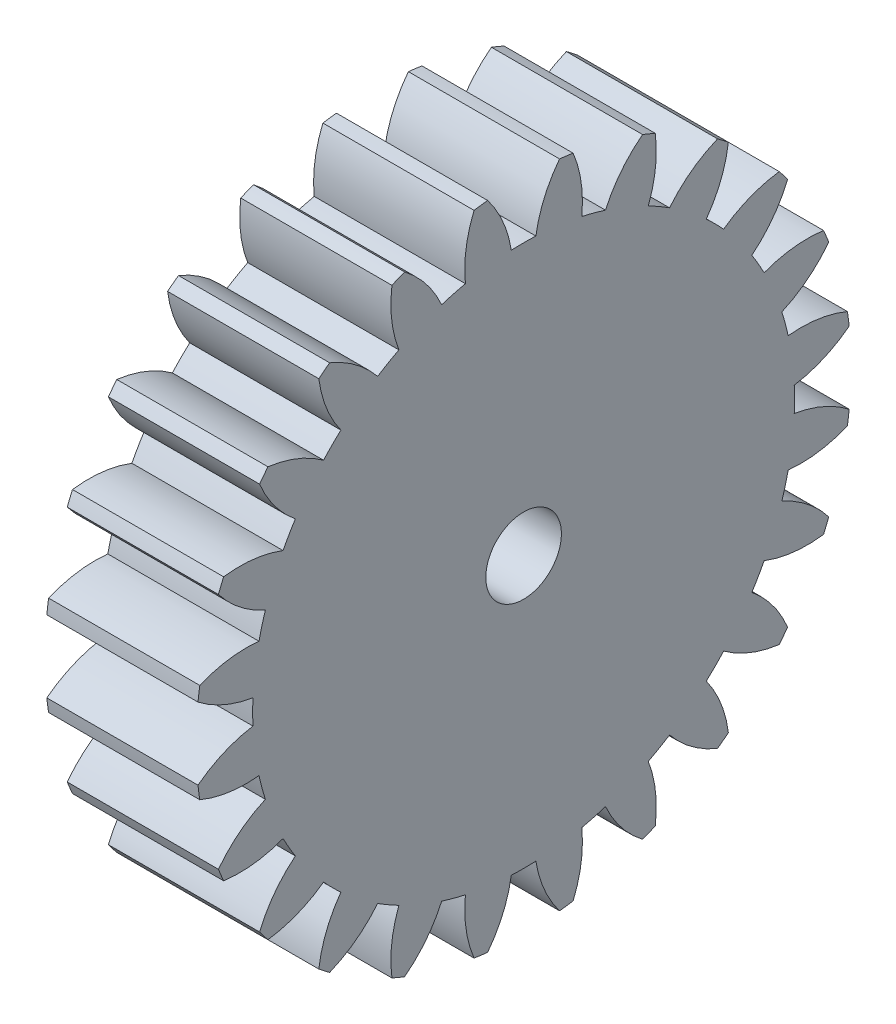
SolidWorks part; units mm, degrees
ref_plane "Plane1" through (0, 0, 0) normal (0, 0, 1) x (1, 0, 0)
ref_plane "Plane2" through (0, 0, 0) normal (0, 1, 0) x (1, 0, 0)
ref_plane "Plane3" through (0, 0, 0) normal (1, 0, 0) x (0, 0, -1)
other "Configuration Table"
sketch "HoldingSke" plane through (0, 0, 0) normal (0, 1, 0) x (1, 0, 0)
  line L0 (0, 0) -> (556.8973, -247.9467)
  line L1 (-15, 0) -> (100, 0) construction
  line L2 (0, 0) -> (-2.1039, 2.3779)
  line L3 (0, 0) -> (-11.863, 4.5341)
  line L4 (0, 0) -> (7.8894, 3.5126)
  line L5 (0, 0) -> (-47.5972, -17.7524)
  line L6 (0, 0) -> (-5.2639, -3.5516)
  line L7 (-2.1039, 2.3779) -> (8.8308, 51.9871)
  line L8 (-76.2, 54.61) -> (-72.771, 54.61)
  line L9 (-71.009, 38.7566) -> (-53.1078, 45.2721)
  line L10 (-76.2, 71.12) -> (104.1128, 71.12)
  line L11 (0, 0) -> (-6.35, 0)
  line L12 (-76.2, 101.6) -> (-76.1573, 101.6)
  line L13 (24.9733, 27.94) -> (52.9518, 28.4284)
  line L14 (24.9733, 27.94) -> (25.0241, 27.9398)
  line L15 (24.9733, 27.94) -> (100.4021, 29.52)
  circle A0 centre (0, 0) radius 1.5875
  circle A1 centre (0, 0) radius 11.3792
  circle A2 centre (0, 0) radius 38.1
  circle A3 centre (0, 0) radius 1.5875
  dimension "MHD" = 22.7584
  dimension "Hub_dia" = 76.2
  dimension "Bore" = 3.175
  dimension "MBD" = 3.175
  dimension "Num_teeth" = 24
  dimension "Pitch" = 609.6
  dimension "Overall_len" = 50.8
  dimension "Show_teeth" = 24
  dimension "Thickness" = 6.35
  dimension "OAL" = 50.8001
  dimension "T_dim" = 3.429
  dimension "Ap" = 20
  dimension "H" = 19.05
  dimension "Pitch_radius" = 180.3128
  dimension "Width" = 6.35
  dimension "Backlash" = 0.0427
  dimension "Addendum_fac" = 1
  dimension "Dedendum_fac" = 1.2
  dimension "Clearance_fac" = 0.2
  dimension "Dedendum_add" = 0.0508
sketch "BasProSke" plane through (0, 0, 0) normal (0, 1, 0) x (1, 0, 0)
  line L0 (-10, 0) -> (60, 0) construction
  line L1 (0, 0) -> (0, 13.7583)
  line L2 (0, 0) -> (6.35, 0)
  line L3 (6.35, 0) -> (6.35, 13.7583)
  line L4 (6.35, 13.7583) -> (0, 13.7583)
  dimension "Thickness" = 6.35
  dimension "Diameter" = 27.5167
revolve "Base-Revolve" add sketch "BasProSke" angle 360 about L0
sketch "TooCutSke" plane through (0, 0, 0) normal (1, 0, 0) x (0, 0, -1)
  line L1 (0, 0) -> (0, 107) construction
  line L2 (0, 0) -> (-0.9053, 12.6677) construction
  line L3 (0, 0) -> (-3.3095, 25.138) construction
  line L4 (-0.9053, 12.6677) -> (-1.6547, 12.569) construction
  arc A0 (0.516, 11.3675) -> (-0.516, 11.3675) centre (0, 0) ccw
  arc A1 (1.5285, 13.6987) -> (-1.5285, 13.6987) centre (0, 0) ccw
  circle A2 centre (0, 0) radius 12.7 construction
  circle A3 centre (0, 0) radius 11.9341 construction
  arc A4 (-0.516, 11.3675) -> (-1.5285, 13.6987) centre (-5.5336, 10.5736) ccw
  arc A5 (1.5285, 13.6987) -> (0.516, 11.3675) centre (5.5336, 10.5736) ccw
  dimension "Root_dia" = 22.7584
  dimension "Overcut_dia" = 27.5675
  dimension "Pitch_dia" = 25.4
  dimension "Base_dia" = 23.8682
  dimension "Flank_rad" = 5.08
  dimension "Half_ang" = 7.5
  dimension "Half_CT" = 0.7559
extrude "ToothCut" cut sketch "TooCutSke" along normal through all
fillet "Breaks" [suppressed] radius 0.0212
fillet "RootFillets" [suppressed] radius 0.2625
pattern_circular "TeethCuts" count 24 every 15 about axis through (-10, 0, 0) along (1, 0, 0) of "ToothCut", "RootFillets", "Breaks"
sketch "HubNeaOneSke" plane through (0, 0, 0) normal (-1, 0, 0) x (0, 0, 1)
  circle A0 centre (0, 0) radius 11.3792
  dimension "Diameter" = 22.7584
extrude "HubNearOne" [suppressed] add sketch "HubNeaOneSke" along normal blind 44.4501
sketch "HubNeaBotSke" plane through (0, 0, 0) normal (-1, 0, 0) x (0, 0, 1)
  circle A0 centre (0, 0) radius 11.3792
  dimension "Diameter" = 22.7584
extrude "HubNearBoth" [suppressed] add sketch "HubNeaBotSke" along normal blind 22.225
ref_plane "FarPln" through (6.35, 0, 0) normal (1, 0, 0) x (0, 0, -1)
sketch "HubFarSke" plane through (6.35, 0, 0) normal (1, 0, 0) x (0, 0, -1)
  circle A0 centre (0, 0) radius 11.3792
  dimension "Diameter" = 22.7584
extrude "HubFar" [suppressed] add sketch "HubFarSke" along normal blind 22.225
sketch "BorSke" plane through (0, 0, 0) normal (1, 0, 0) x (0, 0, -1)
  circle A0 centre (0, 0) radius 1.5875
  dimension "Diameter" = 3.175
extrude "Bore" cut sketch "BorSke" along normal mid plane 101.6001
sketch "KeySke" plane through (0, 0, 0) normal (1, 0, 0) x (0, 0, -1)
  line L0 (-0.127, 0) -> (-0.127, 1.8415)
  line L1 (-0.127, 1.8415) -> (0.127, 1.8415)
  line L2 (0.127, 1.8415) -> (0.127, 0)
  line L3 (0, 0) -> (0, 34) construction
  line L4 (-0.127, 0) -> (0.127, 0)
  dimension "Offset" = 1.8415
  dimension "Width" = 0.254
extrude "Keyway" [suppressed] cut sketch "KeySke" along normal mid plane 101.6001
pattern_circular "Keyway2" [suppressed] count 2 every 90 about axis through (-10, 0, 0) along (1, 0, 0)
sketch "Sketch1" plane through (6.35, 0, 0) normal (1, 0, 0) x (0, 0, -1)
  circle A0 centre (0, 0) radius 5.3367
equation "' \"Pitch@HoldingSke\" = 4"
equation "' \"Num_teeth@HoldingSke\" = 12"
equation "' \"Ap@HoldingSke\" =  20"
equation "' \"Ap@HoldingSke\" = 20"
equation "' \"Width@HoldingSke\" = 0.5"
equation "' \"Hub_dia@HoldingSke\"= 1"
equation "' \"Hub_dia@HoldingSke\" = 1"
equation "' \"Overall_len@HoldingSke\" = 1.0"
equation "' \"Bore@HoldingSke\" = 0.75"
equation "' \"T_dim@HoldingSke\" = 0.85"
equation "' \"Width@KeySke\" = 0.25"
equation "' \"Show_teeth@HoldingSke\" = 13"
equation "' \"Backlash@HoldingSke\" = 0.009"
equation "' \"Addendum_fac@HoldingSke\" = 1.0"
equation "' \"Dedendum_fac@HoldingSke\" = 1.25"
equation "' \"Dedendum_add@HoldingSke\" = 0.00005"
equation "' \"Clearance_fac@HoldingSke\" = 0.25"
equation "' \"Pitch@HoldingSke\" = 0.5"
equation "' \"Num_teeth@HoldingSke\" = 23"
equation "' \"Show_teeth@HoldingSke\" = 23"
equation "' \"Backlash@HoldingSke\" = 0.0375"
equation "\"Overcut_dia@TooCutSke\" = (\"Num_teeth@HoldingSke\" + 2 * \"Addendum_fac@HoldingSke\") / \"Pitch@HoldingSke\" + 0.002"
equation "\"Pitch_dia@TooCutSke\" = \"Num_teeth@HoldingSke\" / \"Pitch@HoldingSke\""
equation "\"Base_dia@TooCutSke\" = \"Num_teeth@HoldingSke\" / \"Pitch@HoldingSke\" * cos((\"Ap@HoldingSke\"  * 3.14159265 / 180))"
equation "\"Root_dia@TooCutSke\" = (\"Num_teeth@HoldingSke\" + 2) / \"Pitch@HoldingSke\" - 2 * (\"Addendum_fac@HoldingSke\" + \"Dedendum_fac@HoldingSke\") / \"Pitch@HoldingSke\" - \"Dedendum_add@HoldingSke\" * 2"
equation "\"Half_ang@TooCutSke\" = 180 / \"Num_teeth@HoldingSke\""
equation "\"Half_CT@TooCutSke\" = \"Num_teeth@HoldingSke\" / \"Pitch@HoldingSke\" * sin((3.14159265 / 2 / \"Num_teeth@HoldingSke\")) / 2 - 7 * \"Backlash@HoldingSke\" / 4"
equation "\"Flank_rad@TooCutSke\" = \"Num_teeth@HoldingSke\" / \"Pitch@HoldingSke\" / 5"
equation "\"Radius@RootFillets\" = \"Clearance_fac@HoldingSke\" / \"Pitch@HoldingSke\" + \"Dedendum_add@HoldingSke\""
equation "\"Break_rad@Breaks\" = 0.02 / \"Pitch@HoldingSke\""
equation "\"Thickness@HoldingSke\" = \"Width@HoldingSke\""
equation "\"OAL@HoldingSke\" = \"Thickness@HoldingSke\""
equation "\"MHD@HoldingSke\" = (\"Num_teeth@HoldingSke\" + 2) / \"Pitch@HoldingSke\" - 2 * (\"Addendum_fac@HoldingSke\" + \"Dedendum_fac@HoldingSke\")  / \"Pitch@HoldingSke\" - \"Dedendum_add@HoldingSke\" * 2"
equation "\"MBD@HoldingSke\" = (\"Num_teeth@HoldingSke\" + 2) / \"Pitch@HoldingSke\" - 2 * (\"Addendum_fac@HoldingSke\" + \"Dedendum_fac@HoldingSke\")  / \"Pitch@HoldingSke\" - \"Dedendum_add@HoldingSke\" * 2 - 0.002"
equation "\"MHD@HoldingSke\" = ((sgn( \"MHD@HoldingSke\" - \"Hub_dia@HoldingSke\" )-1)*( \"MHD@HoldingSke\" - \"Hub_dia@HoldingSke\" ))/-2+ \"Hub_dia@HoldingSke\""
equation "\"MBD@HoldingSke\" = ((sgn( \"MBD@HoldingSke\" - \"Bore@HoldingSke\" )-1)*( \"MBD@HoldingSke\" - \"Bore@HoldingSke\" ))/-2+ \"Bore@HoldingSke\""
equation "\"OAL@HoldingSke\" = ((sgn( \"OAL@HoldingSke\" - \"Overall_len@HoldingSke\" )+1)*( \"OAL@HoldingSke\" - \"Overall_len@HoldingSke\" ))/2 + \"Overall_len@HoldingSke\" + 0.000002"
equation "\"Num_teeth@TeethCuts\" = int( \"Show_teeth@HoldingSke\" ) + 1"
equation "\"Num_teeth@TeethCuts\" = ((sgn( \"Num_teeth@TeethCuts\" - \"Num_teeth@HoldingSke\" )-1)*( \"Num_teeth@TeethCuts\" - \"Num_teeth@HoldingSke\" ))/-2+ \"Num_teeth@HoldingSke\""
equation "\"Num_teeth@TeethCuts\" = ((sgn( \"Num_teeth@TeethCuts\" - 2.0)+1)*( \"Num_teeth@TeethCuts\" - 2.0))/2 +2.0"
equation "\"Angle@TeethCuts\" = 360.0 / \"Num_teeth@HoldingSke\""
equation "\"Diameter@BasProSke\" = (\"Num_teeth@HoldingSke\" + 2 * \"Addendum_fac@HoldingSke\") / \"Pitch@HoldingSke\""
equation "\"Thickness@BasProSke\"  = \"Thickness@HoldingSke\""
equation "' \"Fillet_rad@BasProSke\" =  \"Thickness@HoldingSke\" * 0.05"
equation "' \"Fillet_rad@BasProSke\" = \"Thickness@HoldingSke\" * 0.05"
equation "\"MHD@HoldingSke\" = ((sgn( \"MHD@HoldingSke\" - \"Root_dia@TooCutSke\" )-1)*( \"MHD@HoldingSke\" - \"Root_dia@TooCutSke\" ))/-2+ \"Root_dia@TooCutSke\""
equation "\"Diameter@HubNeaOneSke\" = \"MHD@HoldingSke\""
equation "\"Length@HubNearOne\" = \"OAL@HoldingSke\" - \"Thickness@BasProSke\""
equation "\"Diameter@HubNeaBotSke\" = \"MHD@HoldingSke\""
equation "\"Length@HubNearBoth\" = ( \"OAL@HoldingSke\" - \"Thickness@BasProSke\" ) / 2.0"
equation "\"Thickness@FarPln\" = \"Thickness@BasProSke\""
equation "\"Diameter@HubFarSke\" = \"MHD@HoldingSke\""
equation "\"Length@HubFar\" = ( \"OAL@HoldingSke\" - \"Thickness@BasProSke\" ) / 2.0"
equation "\"Diameter@BorSke\" = \"MBD@HoldingSke\""
equation "\"D1@Bore\" = \"OAL@HoldingSke\" * 2.0"
equation "\"D1@Keyway\" = \"OAL@HoldingSke\" * 2.0"
equation "\"Offset@KeySke\" = \"T_dim@HoldingSke\" - \"MBD@HoldingSke\" / 2.0"
